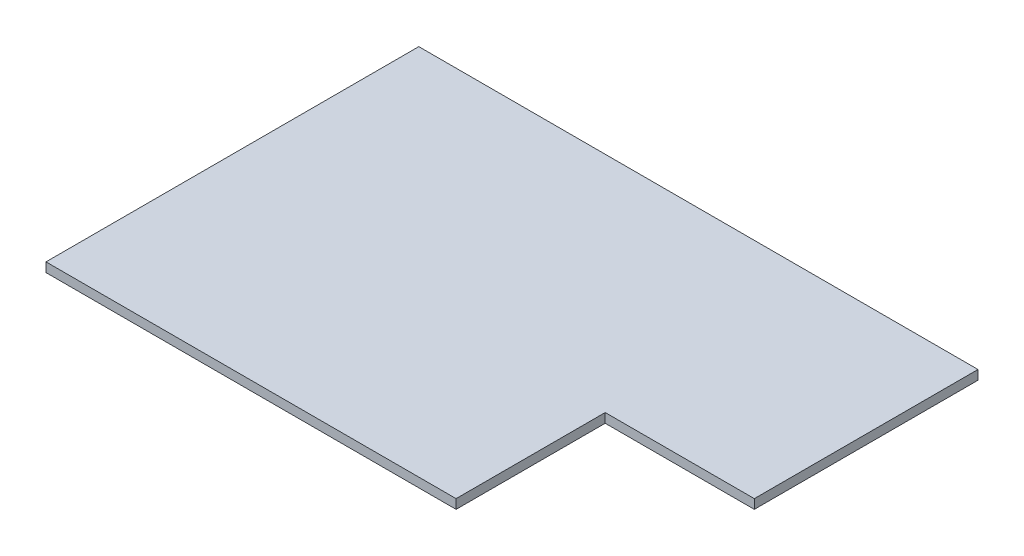
SolidWorks part; units mm, degrees
ref_plane "Front Plane" through (0, 0, 0) normal (0, 0, 1) x (1, 0, 0)
ref_plane "Top Plane" through (0, 0, 0) normal (0, 1, 0) x (1, 0, 0)
ref_plane "Right Plane" through (0, 0, 0) normal (1, 0, 0) x (0, 0, -1)
sketch "Sketch2" plane through (0, 0, 0) normal (0, 1, 0) x (1, 0, 0)
  line L1 (-95.25, -63.5) -> (95.25, -63.5)
  line L2 (-95.25, -63.5) -> (-95.25, 63.5)
  line L3 (-95.25, 63.5) -> (95.25, 63.5)
  line L4 (95.25, -63.5) -> (95.25, 63.5)
  line L5 (-95.25, -63.5) -> (95.25, 63.5) construction
  line L6 (-95.25, 63.5) -> (95.25, -63.5) construction
  point P0 (0, 0)
  dimension "D1" = 127
  dimension "D2" = 190.5
extrude "Boss-Extrude1" add sketch "Sketch2" along normal blind 3.175
sketch "Sketch3" plane through (0, 3.175, 0) normal (0, 1, 0) x (1, 0, 0)
  line L1 (95.25, -63.5) -> (44.45, -63.5)
  line L2 (95.25, -63.5) -> (95.25, -12.7)
  line L3 (95.25, -12.7) -> (44.45, -12.7)
  line L4 (44.45, -63.5) -> (44.45, -12.7)
  dimension "D1" = 50.8
  dimension "D2" = 50.8
extrude "Cut-Extrude1" cut sketch "Sketch3" against normal through all
